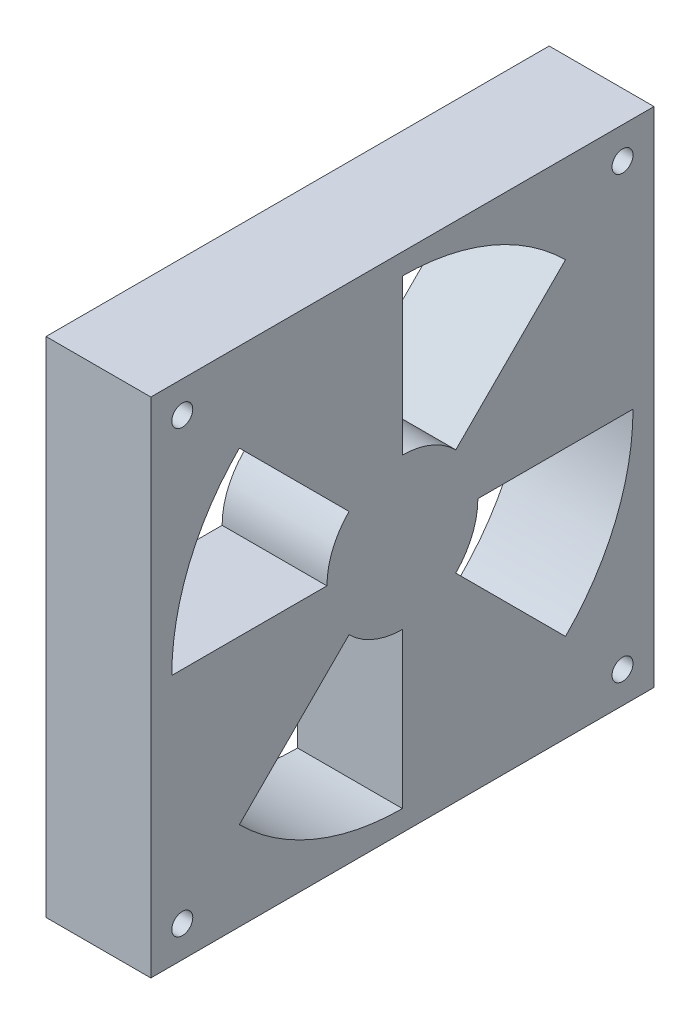
SolidWorks part; units mm, degrees
ref_plane "前视基准面" through (0, 0, 0) normal (0, 0, 1) x (1, 0, 0)
ref_plane "上视基准面" through (0, 0, 0) normal (0, 1, 0) x (1, 0, 0)
ref_plane "右视基准面" through (0, 0, 0) normal (1, 0, 0) x (0, 0, -1)
sketch "草图1" plane through (0, 0, 0) normal (1, 0, 0) x (0, 0, -1)
  line L0 (0, 0) -> (120, 0)
  line L1 (120, 0) -> (120.1799, 0.2628)
  line L2 (0, 0) -> (0, -120)
  line L3 (0, -120) -> (120, -120)
  line L4 (120, 0) -> (120, -120)
  line L5 (72.7279, -47.2721) -> (98.8909, -21.1091)
  line L6 (78, -60) -> (115, -60)
  line L7 (72.7279, -72.7279) -> (98.8909, -98.8909)
  line L8 (60, -78) -> (60, -115)
  line L9 (47.2721, -72.7279) -> (21.1091, -98.8909)
  line L10 (42, -60) -> (5, -60)
  line L11 (60, -42) -> (60, -5)
  line L12 (47.2721, -47.2721) -> (21.1091, -21.1091)
  circle A0 centre (60, -60) radius 55
  circle A1 centre (7.5, -7.5) radius 2.5
  circle A2 centre (112.5, -7.5) radius 2.5
  circle A3 centre (112.5, -112.5) radius 2.5
  circle A4 centre (7.5, -112.5) radius 2.5
  circle A5 centre (60, -60) radius 18
  dimension "D1" = 2
  dimension "D2" = 2
extrude "凸台-拉伸1" add sketch "草图1" along normal blind 25 contours L4 L0 L2 L3 A4 A3 A2 A1 A0 | A5 | A5 L11 A0 L12 | A5 L6 A0 L5 | A5 L8 A0 L7 | A5 L10 A0 L9
